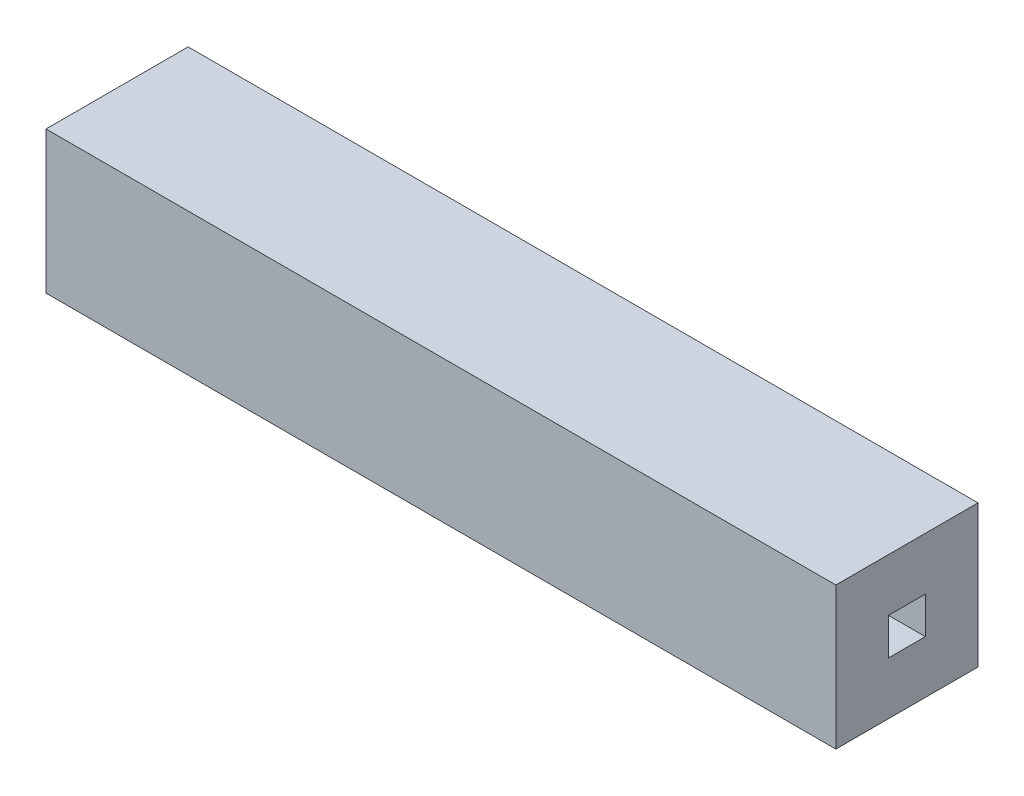
SolidWorks part; units mm, degrees
ref_plane "Front Plane" through (0, 0, 0) normal (0, 0, 1) x (1, 0, 0)
ref_plane "Top Plane" through (0, 0, 0) normal (0, 1, 0) x (1, 0, 0)
ref_plane "Right Plane" through (0, 0, 0) normal (1, 0, 0) x (0, 0, -1)
sketch "Sketch1" plane through (0, 0, 0) normal (1, 0, 0) x (0, 0, -1)
  line L1 (0, 0) -> (2.7, 0)
  line L2 (0, 0) -> (0, 2.7)
  line L3 (0, 2.7) -> (2.7, 2.7)
  line L4 (2.7, 0) -> (2.7, 2.7)
  line L5 (1, 1) -> (1.7, 1)
  line L6 (1, 1) -> (1, 1.7)
  line L7 (1, 1.7) -> (1.7, 1.7)
  line L8 (1.7, 1) -> (1.7, 1.7)
  point P9 (1.35, 2.7)
  point P10 (2.7, 1.35)
  dimension "D1" = 2.7
  dimension "D2" = 2.7
  dimension "D3" = 1
  dimension "D4" = 1
  dimension "D5" = 1
  dimension "D6" = 1
extrude "Boss-Extrude1" add sketch "Sketch1" along normal blind 15
